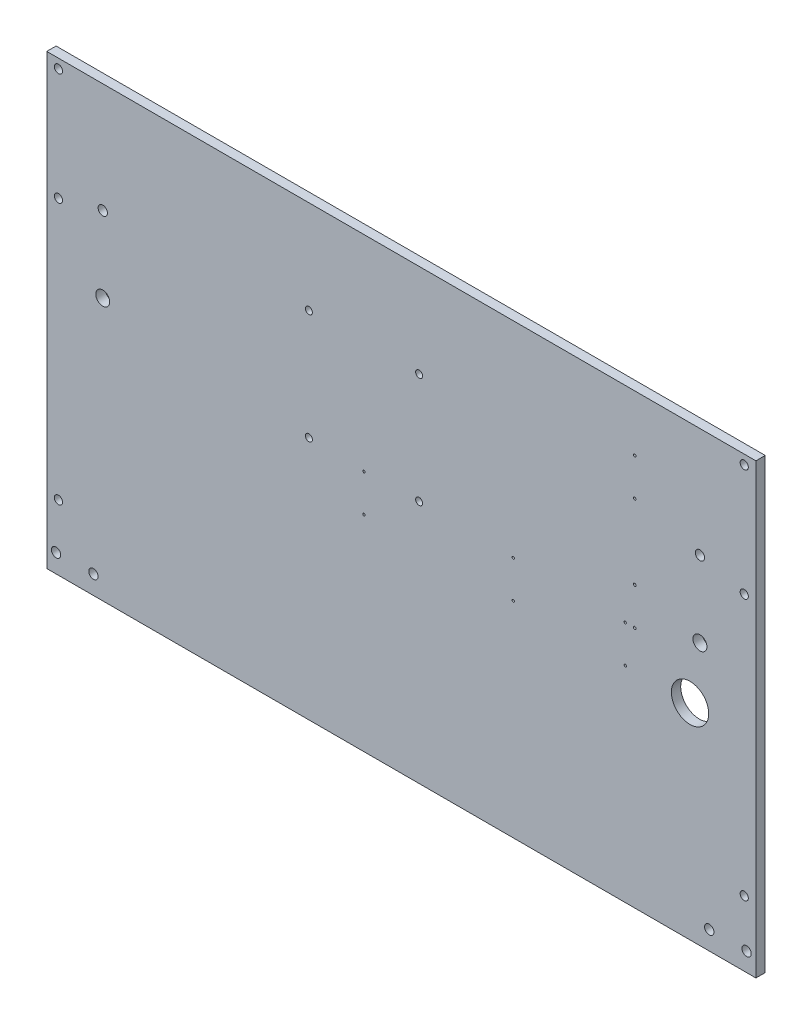
SolidWorks part; units mm, degrees
ref_plane "Front Plane" through (0, 0, 0) normal (0, 0, 1) x (1, 0, 0)
ref_plane "Top Plane" through (0, 0, 0) normal (0, 1, 0) x (1, 0, 0)
ref_plane "Right Plane" through (0, 0, 0) normal (1, 0, 0) x (0, 0, -1)
sketch "Sketch1" plane through (0, 0, 0) normal (0, 0, 1) x (1, 0, 0)
  line L1 (-241.3, -152.4) -> (241.3, -152.4)
  line L2 (-241.3, -152.4) -> (-241.3, 152.4)
  line L3 (-241.3, 152.4) -> (241.3, 152.4)
  line L4 (241.3, -152.4) -> (241.3, 152.4)
  line L5 (-241.3, -152.4) -> (241.3, 152.4) construction
  line L6 (-241.3, 152.4) -> (241.3, -152.4) construction
  point P0 (0, 0)
  dimension "D1" = 482.6
  dimension "D2" = 304.8
extrude "Boss-Extrude1" add sketch "Sketch1" along normal blind 6.35
sketch "Sketch2" plane through (0, 0, 6.35) normal (0, 0, 1) x (1, 0, 0)
  line L0 (-241.3, 0) -> (241.3, 0) construction
  line L1 (-241.3, 152.4) -> (-241.3, -152.4) construction
  line L2 (241.3, -152.4) -> (241.3, 152.4) construction
  line L3 (241.3, 152.4) -> (-241.3, 152.4) construction
  circle A0 centre (-233.3498, 146.05) radius 2.7813
  circle A1 centre (-233.3498, -107.95) radius 2.7813
  circle A2 centre (-233.3498, 69.85) radius 2.7813
  dimension "D2" = 5.5626
  dimension "D3" = 5.5626
  dimension "D6" = 5.5626
  dimension "D1" = 7.9502
  dimension "D4" = 6.35
  dimension "D5" = 254
  dimension "D7" = 76.2
extrude "Cut-Extrude1" cut sketch "Sketch2" against normal through all
mirror "Mirror1" about plane through (0, 0, 0) normal (1, 0, 0) of "Cut-Extrude1"
sketch "Sketch3" plane through (0, 0, 6.35) normal (0, 0, 1) x (1, 0, 0)
  line L0 (-241.3, -139.7) -> (241.3, -139.7) construction
  line L1 (-241.3, 152.4) -> (-241.3, -152.4) construction
  line L2 (241.3, -152.4) -> (241.3, 152.4) construction
  line L3 (-241.3, -152.4) -> (241.3, -152.4) construction
  circle A0 centre (-234.95, -139.7) radius 3.175
  circle A1 centre (-209.55, -139.7) radius 3.175
  dimension "D2" = 6.35
  dimension "D3" = 6.35
  dimension "D4" = 25.4
  dimension "D5" = 6.35
  dimension "D1" = 12.7
extrude "Cut-Extrude2" cut sketch "Sketch3" against normal through all
mirror "Mirror2" about plane through (0, 0, 0) normal (1, 0, 0) of "Cut-Extrude2"
sketch "Sketch4" plane through (0, 0, 6.35) normal (0, 0, 1) x (1, 0, 0)
  line L0 (241.3, 152.4) -> (-241.3, 152.4) construction
  circle A0 centre (196.469, -12.7) radius 12.7
  dimension "D2" = 25.4
  dimension "D1" = 196.469
  dimension "D3" = 165.1
extrude "Cut-Extrude3" cut sketch "Sketch4" against normal through all
sketch "Sketch5" plane through (0, 0, 6.35) normal (0, 0, 1) x (1, 0, 0)
  line L0 (241.3, 152.4) -> (-241.3, 152.4) construction
  line L1 (-62.9, 13.9) -> (12.1, 13.9) construction
  line L2 (-62.9, 13.9) -> (-62.9, 88.9) construction
  line L3 (-62.9, 88.9) -> (12.1, 88.9) construction
  line L4 (12.1, 13.9) -> (12.1, 88.9) construction
  line L5 (-62.9, 13.9) -> (12.1, 88.9) construction
  line L6 (-62.9, 88.9) -> (12.1, 13.9) construction
  circle A0 centre (-62.9, 88.9) radius 2.3749
  circle A1 centre (12.1, 88.9) radius 2.3749
  circle A2 centre (12.1, 13.9) radius 2.3749
  circle A3 centre (-62.9, 13.9) radius 2.3749
  point P0 (-25.4, 51.4)
  dimension "D4" = 4.7498
  dimension "D5" = 4.7498
  dimension "D6" = 4.7498
  dimension "D7" = 4.7498
  dimension "D1" = 75
  dimension "D2" = 75
  dimension "D3" = 63.5
  dimension "D8" = 25.4
extrude "Cut-Extrude4" cut sketch "Sketch5" against normal through all
sketch "Sketch6" plane through (0, 0, 6.35) normal (0, 0, 1) x (1, 0, 0)
  line L0 (241.3, -152.4) -> (241.3, 152.4) construction
  line L1 (-241.3, 152.4) -> (-241.3, -152.4) construction
  circle A0 centre (-203.2, 77.7271) radius 3.175
  circle A1 centre (-203.2, 26.0961) radius 4.7625
  circle A2 centre (203.2, 77.7271) radius 3.175
  circle A3 centre (203.2, 26.0961) radius 4.7625
  dimension "D1" = 6.35
  dimension "D2" = 6.35
  dimension "D3" = 9.525
  dimension "D4" = 9.525
  dimension "D5" = 38.1
  dimension "D6" = 38.1
extrude "Cut-Extrude5" cut sketch "Sketch6" against normal through all
sketch "Sketch7" plane through (0, 0, 6.35) normal (0, 0, 1) x (1, 0, 0)
  line L0 (158.8215, 152.4) -> (158.8215, -152.4) construction
  line L1 (241.3, 152.4) -> (-241.3, 152.4) construction
  line L2 (-241.3, -152.4) -> (241.3, -152.4) construction
  circle A0 centre (158.8215, 114.3) radius 0.889
  circle A1 centre (158.8215, 88.9) radius 0.889
  circle A2 centre (158.8215, 38.1) radius 0.889
  circle A3 centre (158.8215, 12.7) radius 0.889
  dimension "D1" = 1.778
  dimension "D2" = 1.778
  dimension "D3" = 1.778
  dimension "D4" = 1.778
  dimension "D8" = 38.1
  dimension "D5" = 25.4
  dimension "D6" = 25.4
  dimension "D7" = 50.8
extrude "Cut-Extrude6" cut sketch "Sketch7" against normal through all
sketch "Sketch8" plane through (0, 0, 6.35) normal (0, 0, 1) x (1, 0, 0)
  circle A0 centre (-25.4, 12.7) radius 0.8255
  circle A1 centre (-25.4, -12.7) radius 0.8255
  circle A2 centre (76.2, 12.7) radius 0.7937
  circle A3 centre (76.2, -12.7) radius 0.7937
  circle A4 centre (152.4, 12.7) radius 0.7937
  circle A5 centre (152.4, -12.7) radius 0.7937
  dimension "D1" = 1.651
  dimension "D2" = 1.651
  dimension "D7" = 1.5875
  dimension "D8" = 1.5875
  dimension "D9" = 1.5875
  dimension "D10" = 1.5875
  dimension "D3" = 25.4
  dimension "D4" = 12.7
  dimension "D5" = 25.4
  dimension "D6" = 101.6
  dimension "D11" = 76.2
extrude "Cut-Extrude7" cut sketch "Sketch8" against normal through all
